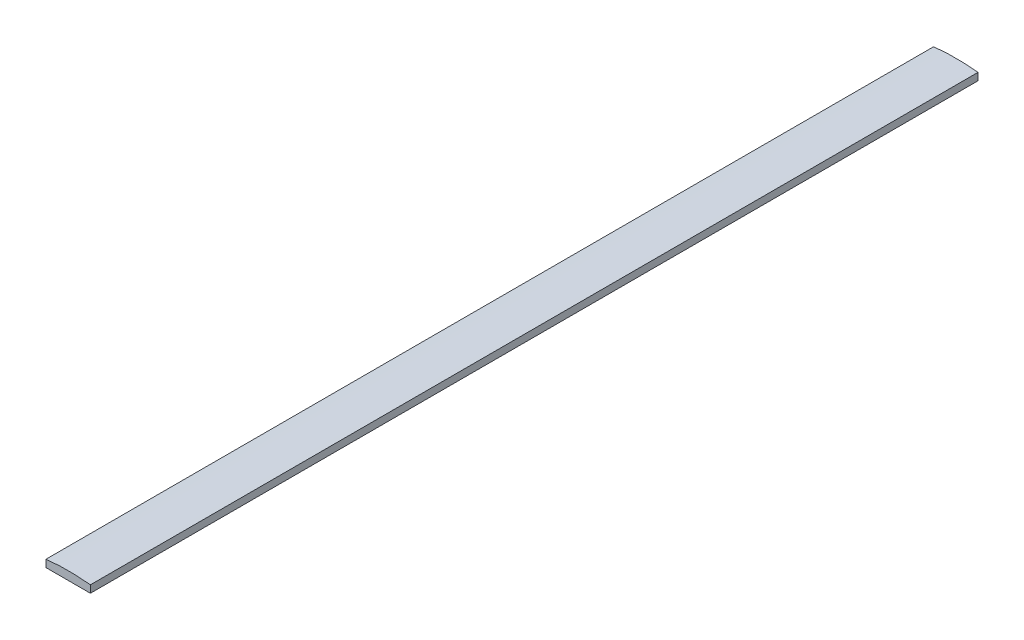
SolidWorks part; units mm, degrees
ref_plane "Ebene vorne" through (0, 0, 0) normal (0, 0, 1) x (1, 0, 0)
ref_plane "Ebene oben" through (0, 0, 0) normal (0, 1, 0) x (1, 0, 0)
ref_plane "Ebene rechts" through (0, 0, 0) normal (1, 0, 0) x (0, 0, -1)
sketch "Skizze1" plane through (0, 0, 0) normal (0, 0, 1) x (1, 0, 0)
  line L2 (-12.6536, 5.0835) -> (-12.6536, 2.3575)
  line L3 (-12.6536, 2.3575) -> (3.8464, 2.3575)
  line L4 (3.8464, 5.0835) -> (3.8464, 2.3575)
  arc A0 (3.8464, 5.0835) -> (-12.6536, 5.0835) centre (-4.4036, -70.4674) ccw
  dimension "D1" = 152
  dimension "D2" = 16.5
  dimension "D3" = 2.726
extrude "Aufsatz-Linear austragen1" add sketch "Skizze1" along normal blind 330
